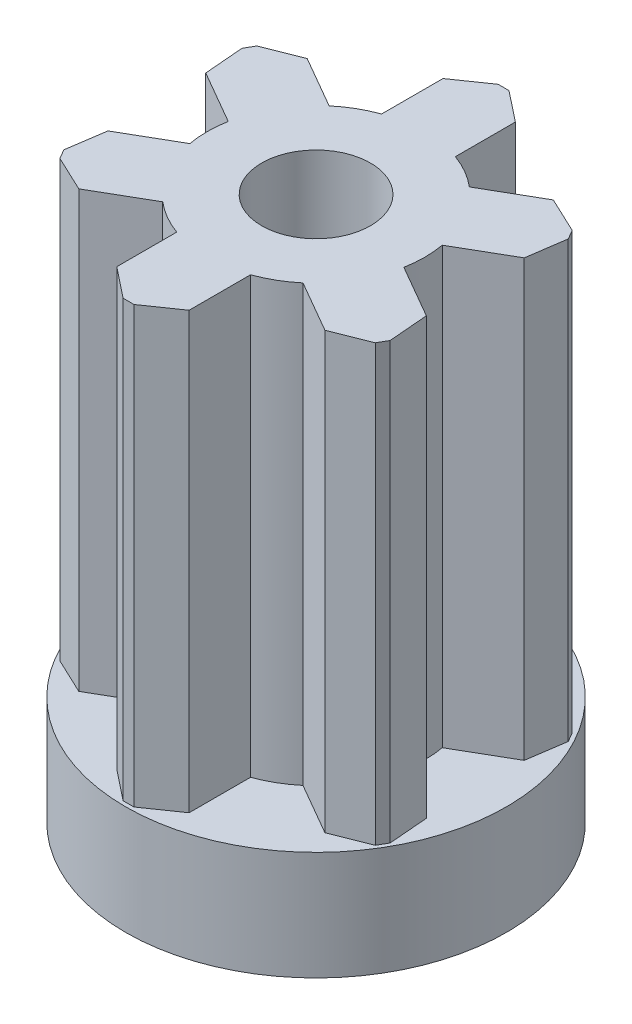
SolidWorks part; units mm, degrees
ref_plane "Front Plane" through (0, 0, 0) normal (0, 0, 1) x (1, 0, 0)
ref_plane "Top Plane" through (0, 0, 0) normal (0, 1, 0) x (1, 0, 0)
ref_plane "Right Plane" through (0, 0, 0) normal (1, 0, 0) x (0, 0, -1)
sketch "Sketch1" plane through (0, 0, 0) normal (0, 1, 0) x (1, 0, 0)
  circle A0 centre (0, 0) radius 1.75
  dimension "D1" = 3.5
extrude "Boss-Extrude1" add sketch "Sketch1" along normal blind 1
sketch "Sketch2" plane through (0, 1, 0) normal (0, 1, 0) x (1, 0, 0)
  circle A0 centre (0, 0) radius 1
sketch "Sketch3" plane through (0, 1, 0) normal (0, 1, 0) x (1, 0, 0)
  line L0 (-0.3388, 0.9253) -> (-0.3388, 1.5056)
  line L1 (-0.3388, 1.5056) -> (-0.0394, 1.713)
  line L2 (-0.0394, 1.713) -> (0.0604, 1.713)
  line L3 (0.0604, 1.713) -> (0.34, 1.4916)
  line L4 (0.34, 1.4916) -> (0.34, 0.9253)
  line L5 (0.34, 0.9253) -> (-0.3388, 0.9253)
  line L6 (0, 0) -> (0, 2.2106) construction
  line L7 (0.34, 0.9253) -> (0.34, 1.8848) construction
  line L8 (-0.3388, 0.9253) -> (-0.3388, 1.8421) construction
  point P3 (-0.0394, 1.713)
  point P10 (0, 0)
  point P12 (-0.3388, 0.9253)
  point P13 (0, 0)
  point P14 (0.367, 0.9253)
  dimension "D1" = 0.3388
  dimension "D2" = 0.34
extrude "Boss-Extrude4" add sketch "Sketch3" along normal blind 4
extrude "Boss-Extrude5" add sketch "Sketch2" along normal blind 4 contours A0
pattern_circular "CirPattern1" count 6 over 360 about axis through (0, 0, 0) along (0, 1, 0) of "Boss-Extrude4"
sketch "Sketch4" plane through (0, 5, 0) normal (0, 1, 0) x (1, 0, 0)
  circle A0 centre (0, 0) radius 0.5
  dimension "D1" = 1
extrude "Cut-Extrude1" cut sketch "Sketch4" against normal through all
